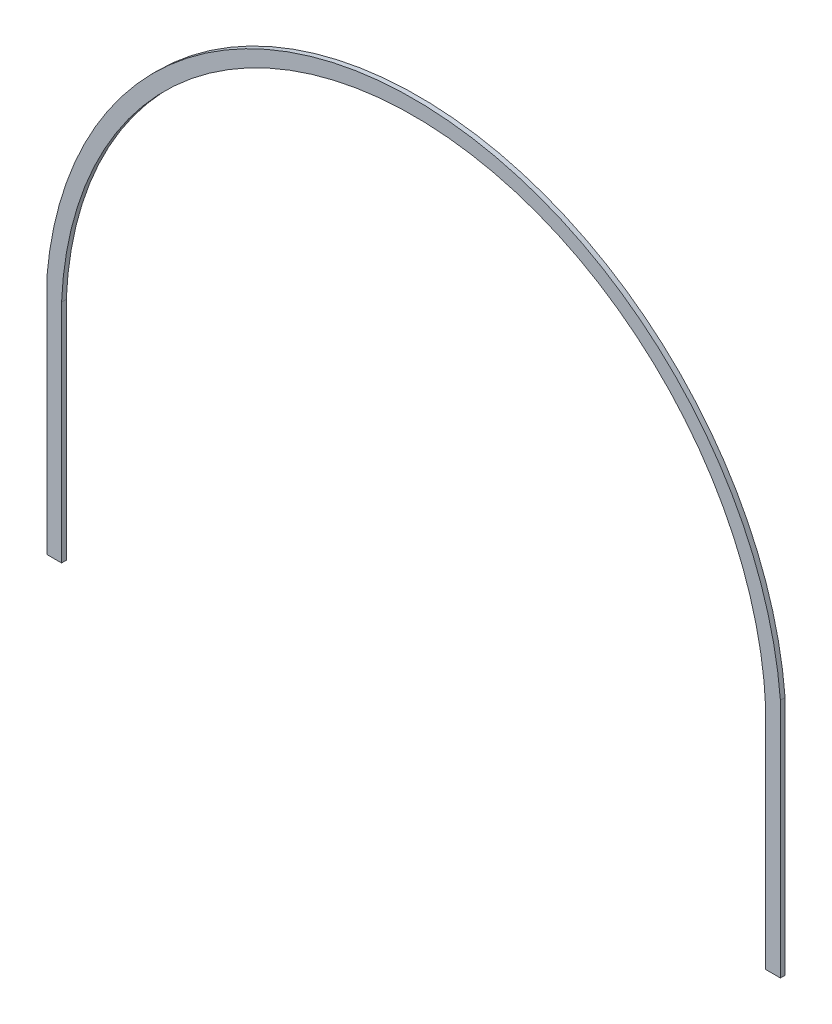
SolidWorks part; units mm, degrees
ref_plane "Plan de face" through (0, 0, 0) normal (0, 0, 1) x (1, 0, 0)
ref_plane "Plan de dessus" through (0, 0, 0) normal (0, 1, 0) x (1, 0, 0)
ref_plane "Plan de droite" through (0, 0, 0) normal (1, 0, 0) x (0, 0, -1)
sketch "Esquisse1" plane through (0, 0, 0) normal (0, 0, 1) x (1, 0, 0)
  line L2 (0, 0) -> (0, 197) construction
  line L3 (0, 197) -> (250, 197) construction
  line L4 (250, 0) -> (250, 197) construction
  line L6 (5, 0) -> (5, 77)
  line L8 (245, 0) -> (245, 77)
  line L14 (0, 0) -> (5, 0)
  line L15 (250, 0) -> (245, 0)
  line L16 (5, 77) -> (5, 197) construction
  line L17 (0, 0) -> (0, 82)
  line L18 (250, 0) -> (250, 82)
  line L19 (125, 192) -> (125, 197) construction
  arc A2 (0, 82) -> (250, 82) centre (125, 71.5652) cw
  arc A3 (245, 77) -> (5, 77) centre (125, 71.8913) ccw
  point P14 (125, 197)
extrude "Boss.-Extru.1" add sketch "Esquisse1" along normal blind 1.6
sketch "Esquisse2" plane through (0, 0, 1.6) normal (0, 0, 1) x (1, 0, 0)
  arc A0 (250, 82) -> (0, 82) centre (125, 71.5652) ccw construction
  point P0 (125, 197)
